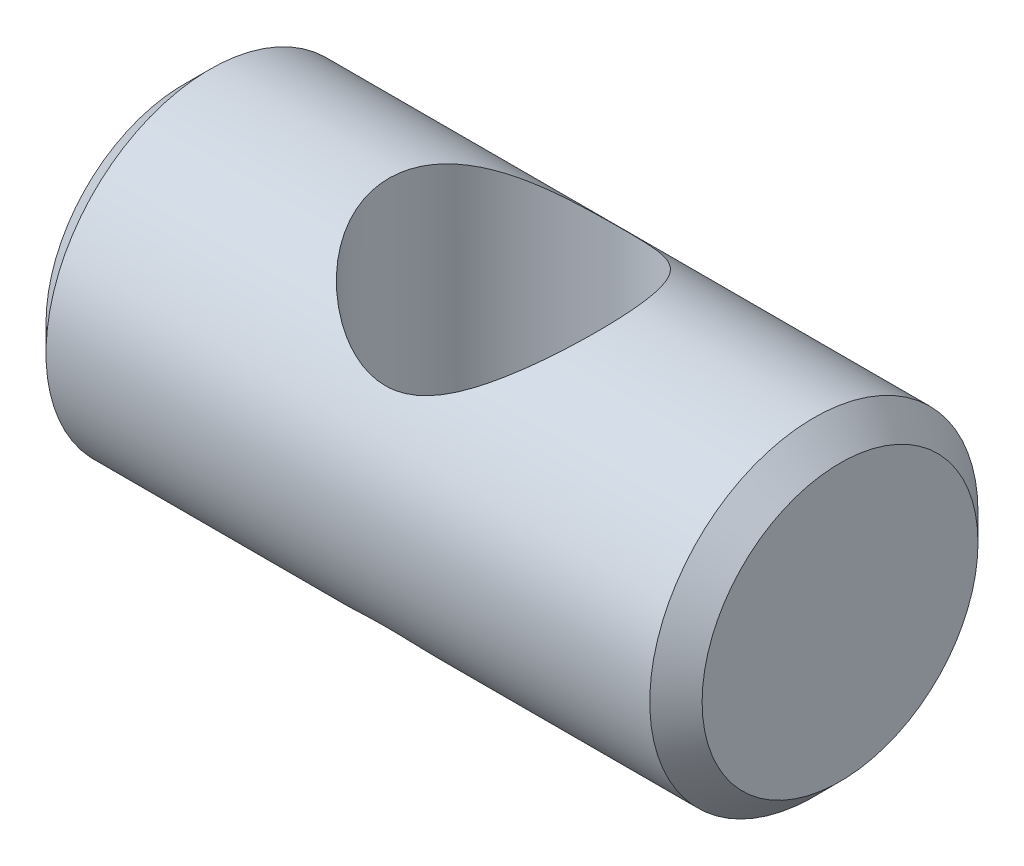
SolidWorks part; units mm, degrees
ref_plane "Front Plane" through (0, 0, 0) normal (0, 0, 1) x (1, 0, 0)
ref_plane "Top Plane" through (0, 0, 0) normal (0, 1, 0) x (1, 0, 0)
ref_plane "Right Plane" through (0, 0, 0) normal (1, 0, 0) x (0, 0, -1)
sketch "Sketch1" plane through (0, 0, 0) normal (1, 0, 0) x (0, 0, -1)
  circle A0 centre (0, 0) radius 4.765
  dimension "D1" = 9.53
extrude "Boss-Extrude1" add sketch "Sketch1" along normal mid plane 19.05
chamfer "Chamfer1" distance 0.76 angle 45 2 edges at (-9.525, 0, -4.765) (9.525, 0, -4.765)
sketch "Sketch2" plane through (0, 0, 0) normal (0, 1, 0) x (1, 0, 0)
  circle A0 centre (0, -0.25) radius 3.43
  dimension "D1" = 6.86
  dimension "D2" = 0.25
extrude "Cut-Extrude1" cut sketch "Sketch2" against normal mid plane 19.05
